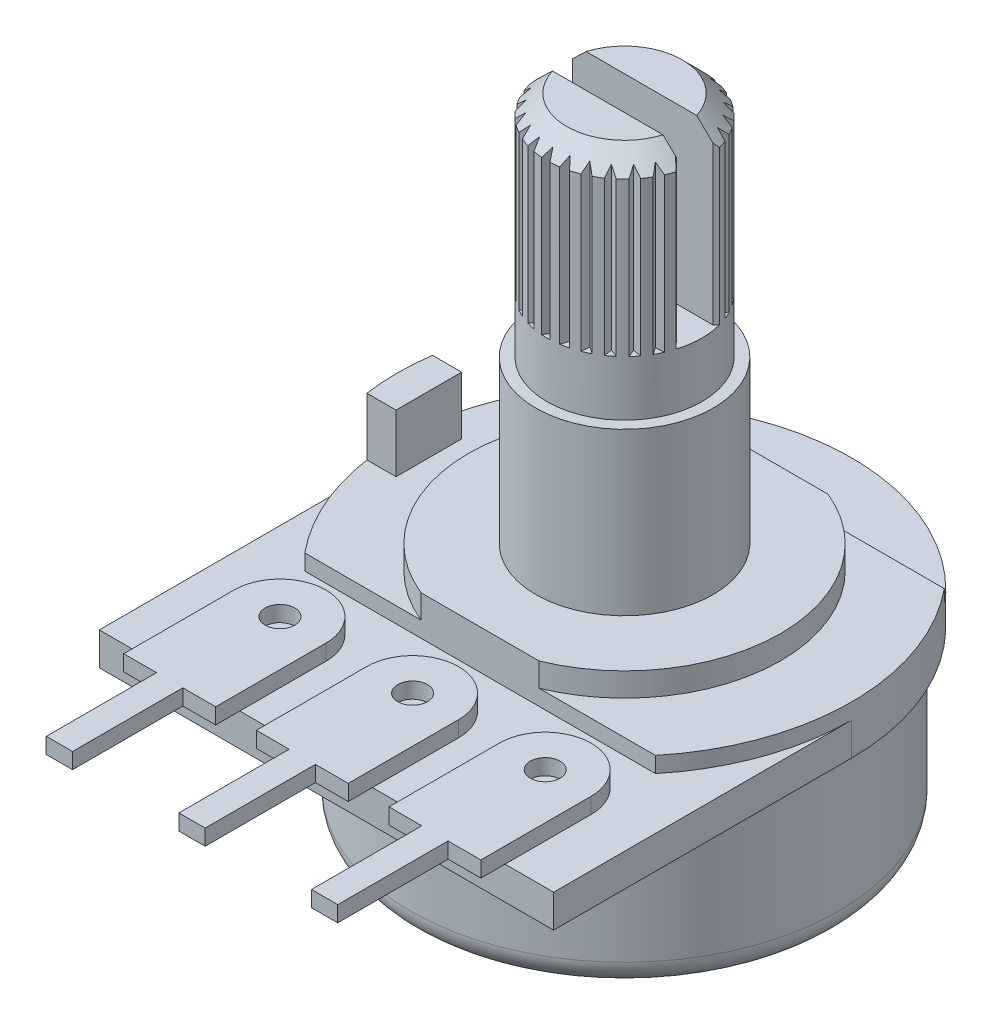
SolidWorks part; units mm, degrees
ref_plane "Alzado" through (0, 0, 0) normal (0, 0, 1) x (1, 0, 0)
ref_plane "Planta" through (0, 0, 0) normal (0, 1, 0) x (1, 0, 0)
ref_plane "Vista lateral" through (0, 0, 0) normal (1, 0, 0) x (0, 0, -1)
sketch "Croquis1" plane through (0, 0, 0) normal (0, 1, 0) x (1, 0, 0)
  circle A0 centre (0, 0) radius 8.15
  dimension "D1" = 16.3
extrude "Saliente-Extruir1" add sketch "Croquis1" along normal blind 6.3
fillet "Redondeo1" radius 1 1 edges at (0, 0, 8.15)
sketch "Croquis2" plane through (0, 6.3, 0) normal (0, 1, 0) x (1, 0, 0)
  line L0 (-8.65, 0) -> (-8.65, -11.35)
  line L1 (-8.65, -11.35) -> (8.65, -11.35)
  line L2 (8.65, -11.35) -> (8.65, 0)
  arc A0 (-8.65, 0) -> (8.65, 0) centre (0, 0) cw
  dimension "D1" = 8.65
  dimension "D2" = 11.35
extrude "Saliente-Extruir2" add sketch "Croquis2" along normal blind 1.25
sketch "Croquis11" plane through (0, 0, 0) normal (0, -1, 0) x (1, 0, 0)
  line L1 (-10.6457, -1) -> (-6.6543, -1)
  line L2 (-10.6457, -1) -> (-10.6457, 1)
  line L3 (-10.6457, 1) -> (-6.6543, 1)
  line L4 (-6.6543, -1) -> (-6.6543, 1)
  line L5 (-10.6457, -1) -> (-6.6543, 1) construction
  line L6 (-10.6457, 1) -> (-6.6543, -1) construction
  point P0 (-8.65, 0)
  dimension "D1" = 2
extrude "Cortar-Extruir3" cut sketch "Croquis11" against normal blind 2.6
sketch "Croquis3" plane through (0, 7.55, 0) normal (0, 1, 0) x (1, 0, 0)
  line L0 (-5.55, -16.47) -> (-5.55, -12.27)
  line L1 (-5.55, -12.27) -> (-6.8, -12.27)
  line L2 (-6.8, -12.27) -> (-6.8, -8.07)
  line L3 (-3.3, -8.07) -> (-3.3, -12.27)
  line L4 (-3.3, -12.27) -> (-4.55, -12.27)
  line L5 (-4.55, -12.27) -> (-4.55, -16.47)
  line L6 (-4.55, -16.47) -> (-5.55, -16.47)
  line L7 (-8.65, -11.35) -> (8.65, -11.35) construction
  line L8 (-0.5, -16.47) -> (-0.5, -12.27)
  line L9 (-0.5, -12.27) -> (-1.75, -12.27)
  line L10 (-1.75, -12.27) -> (-1.75, -8.07)
  line L11 (1.75, -8.07) -> (1.75, -12.27)
  line L12 (1.75, -12.27) -> (0.5, -12.27)
  line L13 (0.5, -12.27) -> (0.5, -16.47)
  line L14 (0.5, -16.47) -> (-0.5, -16.47)
  line L15 (4.55, -16.47) -> (4.55, -12.27)
  line L16 (4.55, -12.27) -> (3.3, -12.27)
  line L17 (3.3, -12.27) -> (3.3, -8.07)
  line L18 (6.8, -8.07) -> (6.8, -12.27)
  line L19 (6.8, -12.27) -> (5.55, -12.27)
  line L20 (5.55, -12.27) -> (5.55, -16.47)
  line L21 (5.55, -16.47) -> (4.55, -16.47)
  arc A0 (-6.8, -8.07) -> (-3.3, -8.07) centre (-5.05, -8.07) cw
  circle A1 centre (-5.05, -8.07) radius 0.5655
  arc A2 (-1.75, -8.07) -> (1.75, -8.07) centre (0, -8.07) cw
  circle A3 centre (0, -8.07) radius 0.5655
  arc A4 (3.3, -8.07) -> (6.8, -8.07) centre (5.05, -8.07) cw
  circle A5 centre (5.05, -8.07) radius 0.5655
  point P13 (0, -11.35)
  dimension "D1" = 1.75
  dimension "D2" = 1
  dimension "D3" = 4.2
  dimension "D4" = 5.12
  dimension "D5" = 4.2
  dimension "D6" = 3
extrude "Saliente-Extruir3" add sketch "Croquis3" along normal blind 0.6 separate body
sketch "Croquis4" plane through (0, 7.55, 0) normal (0, 1, 0) x (1, 0, 0)
  line L0 (-6.6763, -5.5) -> (6.6763, -5.5)
  line L1 (-6.6763, 5.5) -> (6.6763, 5.5)
  arc A0 (-6.6763, 5.5) -> (-6.6763, -5.5) centre (0, 0) ccw
  arc A1 (8.65, 0) -> (-8.65, 0) centre (0, 0) ccw construction
  arc A2 (6.6763, 5.5) -> (6.6763, -5.5) centre (0, 0) cw
  dimension "D1" = 11
extrude "Saliente-Extruir4" add sketch "Croquis4" along normal blind 0.6
sketch "Croquis5" plane through (0, 8.15, 0) normal (0, 1, 0) x (1, 0, 0)
  line L0 (6.6763, 5.5) -> (-6.6763, 5.5) construction
  line L1 (-6.6763, -5.5) -> (6.6763, -5.5) construction
  line L2 (-2.25, 5.5) -> (2.25, 5.5)
  line L3 (-2.25, -5.5) -> (2.25, -5.5)
  line L4 (-6.6763, -5.5) -> (6.6763, -5.5) construction
  arc A0 (-2.25, -5.5) -> (-2.25, 5.5) centre (0, 0) cw
  arc A1 (2.25, 5.5) -> (2.25, -5.5) centre (0, 0) cw
  dimension "D1" = 4.5
extrude "Saliente-Extruir5" add sketch "Croquis5" along normal blind 0.9
sketch "Croquis6" plane through (0, 9.05, 0) normal (0, 1, 0) x (1, 0, 0)
  circle A0 centre (0, 0) radius 3.375
  dimension "D1" = 6.75
extrude "Saliente-Extruir6" add sketch "Croquis6" along normal blind 6.15
sketch "Croquis7" plane through (0, 15.2, 0) normal (0, 1, 0) x (1, 0, 0)
  circle A0 centre (0, 0) radius 2.95
  dimension "D1" = 5.9
extrude "Saliente-Extruir7" add sketch "Croquis7" along normal blind 8.7
chamfer "Chaflán1" distance 0.75 angle 45 1 edges at (0, 23.9, 2.95)
sketch "Croquis8" plane through (0, 23.9, 0) normal (0, 1, 0) x (1, 0, 0)
  line L1 (-6.8143, 0.64) -> (6.8143, 0.64)
  line L2 (-6.8143, 0.64) -> (-6.8143, -0.64)
  line L3 (-6.8143, -0.64) -> (6.8143, -0.64)
  line L4 (6.8143, 0.64) -> (6.8143, -0.64)
  line L5 (-6.8143, 0.64) -> (6.8143, -0.64) construction
  line L6 (-6.8143, -0.64) -> (6.8143, 0.64) construction
  point P0 (0, 0)
  dimension "D1" = 1.28
extrude "Cortar-Extruir1" cut sketch "Croquis8" against normal blind 6.6
sketch "Croquis9" plane through (0, 23.9, 0) normal (0, 1, 0) x (1, 0, 0)
  line L0 (0.0546, 2.67) -> (0.314, 3.1192)
  line L1 (0.314, 3.1192) -> (-0.2048, 3.1192)
  line L2 (-0.2048, 3.1192) -> (0.0546, 2.67)
  line L3 (0.6474, 2.5909) -> (1.0002, 2.9712)
  line L4 (1.0002, 2.9712) -> (0.4944, 3.0866)
  line L5 (0.4944, 3.0866) -> (0.6474, 2.5909)
  line L6 (1.2077, 2.3819) -> (1.6363, 2.6741)
  line L7 (1.6363, 2.6741) -> (1.1689, 2.8992)
  line L8 (1.1689, 2.8992) -> (1.2077, 2.3819)
  line L9 (1.7074, 2.0534) -> (2.1903, 2.2429)
  line L10 (2.1903, 2.2429) -> (1.7847, 2.5664)
  line L11 (1.7847, 2.5664) -> (1.7074, 2.0534)
  line L12 (2.1215, 1.622) -> (2.6345, 1.6993)
  line L13 (2.6345, 1.6993) -> (2.311, 2.1049)
  line L14 (2.311, 2.1049) -> (2.1215, 1.622)
  line L15 (2.4292, 1.1093) -> (2.9466, 1.0705)
  line L16 (2.9466, 1.0705) -> (2.7215, 1.5379)
  line L17 (2.7215, 1.5379) -> (2.4292, 1.1093)
  line L18 (2.6152, 0.5409) -> (3.1109, 0.388)
  line L19 (3.1109, 0.388) -> (2.9955, 0.8937)
  line L20 (2.9955, 0.8937) -> (2.6152, 0.5409)
  line L21 (2.67, -0.0546) -> (3.1192, -0.314)
  line L22 (3.1192, -0.314) -> (3.1192, 0.2048)
  line L23 (3.1192, 0.2048) -> (2.67, -0.0546)
  line L24 (2.5909, -0.6474) -> (2.9712, -1.0002)
  line L25 (2.9712, -1.0002) -> (3.0866, -0.4944)
  line L26 (3.0866, -0.4944) -> (2.5909, -0.6474)
  line L27 (2.3819, -1.2077) -> (2.6741, -1.6363)
  line L28 (2.6741, -1.6363) -> (2.8992, -1.1689)
  line L29 (2.8992, -1.1689) -> (2.3819, -1.2077)
  line L30 (2.0534, -1.7074) -> (2.2429, -2.1903)
  line L31 (2.2429, -2.1903) -> (2.5664, -1.7847)
  line L32 (2.5664, -1.7847) -> (2.0534, -1.7074)
  line L33 (1.622, -2.1215) -> (1.6993, -2.6345)
  line L34 (1.6993, -2.6345) -> (2.1049, -2.311)
  line L35 (2.1049, -2.311) -> (1.622, -2.1215)
  line L36 (1.1093, -2.4292) -> (1.0705, -2.9466)
  line L37 (1.0705, -2.9466) -> (1.5379, -2.7215)
  line L38 (1.5379, -2.7215) -> (1.1093, -2.4292)
  line L39 (0.5409, -2.6152) -> (0.388, -3.1109)
  line L40 (0.388, -3.1109) -> (0.8937, -2.9955)
  line L41 (0.8937, -2.9955) -> (0.5409, -2.6152)
  line L42 (-0.0546, -2.67) -> (-0.314, -3.1192)
  line L43 (-0.314, -3.1192) -> (0.2048, -3.1192)
  line L44 (0.2048, -3.1192) -> (-0.0546, -2.67)
  line L45 (-0.6474, -2.5909) -> (-1.0002, -2.9712)
  line L46 (-1.0002, -2.9712) -> (-0.4944, -3.0866)
  line L47 (-0.4944, -3.0866) -> (-0.6474, -2.5909)
  line L48 (-1.2077, -2.3819) -> (-1.6363, -2.6741)
  line L49 (-1.6363, -2.6741) -> (-1.1689, -2.8992)
  line L50 (-1.1689, -2.8992) -> (-1.2077, -2.3819)
  line L51 (-1.7074, -2.0534) -> (-2.1903, -2.2429)
  line L52 (-2.1903, -2.2429) -> (-1.7847, -2.5664)
  line L53 (-1.7847, -2.5664) -> (-1.7074, -2.0534)
  line L54 (-2.1215, -1.622) -> (-2.6345, -1.6993)
  line L55 (-2.6345, -1.6993) -> (-2.311, -2.1049)
  line L56 (-2.311, -2.1049) -> (-2.1215, -1.622)
  line L57 (-2.4292, -1.1093) -> (-2.9466, -1.0705)
  line L58 (-2.9466, -1.0705) -> (-2.7215, -1.5379)
  line L59 (-2.7215, -1.5379) -> (-2.4292, -1.1093)
  line L60 (-2.6152, -0.5409) -> (-3.1109, -0.388)
  line L61 (-3.1109, -0.388) -> (-2.9955, -0.8937)
  line L62 (-2.9955, -0.8937) -> (-2.6152, -0.5409)
  line L63 (-2.67, 0.0546) -> (-3.1192, 0.314)
  line L64 (-3.1192, 0.314) -> (-3.1192, -0.2048)
  line L65 (-3.1192, -0.2048) -> (-2.67, 0.0546)
  line L66 (-2.5909, 0.6474) -> (-2.9712, 1.0002)
  line L67 (-2.9712, 1.0002) -> (-3.0866, 0.4944)
  line L68 (-3.0866, 0.4944) -> (-2.5909, 0.6474)
  line L69 (-2.3819, 1.2077) -> (-2.6741, 1.6363)
  line L70 (-2.6741, 1.6363) -> (-2.8992, 1.1689)
  line L71 (-2.8992, 1.1689) -> (-2.3819, 1.2077)
  line L72 (-2.0534, 1.7074) -> (-2.2429, 2.1903)
  line L73 (-2.2429, 2.1903) -> (-2.5664, 1.7847)
  line L74 (-2.5664, 1.7847) -> (-2.0534, 1.7074)
  line L75 (-1.622, 2.1215) -> (-1.6993, 2.6345)
  line L76 (-1.6993, 2.6345) -> (-2.1049, 2.311)
  line L77 (-2.1049, 2.311) -> (-1.622, 2.1215)
  line L78 (-1.1093, 2.4292) -> (-1.0705, 2.9466)
  line L79 (-1.0705, 2.9466) -> (-1.5379, 2.7215)
  line L80 (-1.5379, 2.7215) -> (-1.1093, 2.4292)
  line L81 (-0.5409, 2.6152) -> (-0.388, 3.1109)
  line L82 (-0.388, 3.1109) -> (-0.8937, 2.9955)
  line L83 (-0.8937, 2.9955) -> (-0.5409, 2.6152)
  point P2 (0.0546, 3.1192)
  point P88 (0, 0)
  dimension "D1" = 60
  dimension "D2" = 28
extrude "Cortar-Extruir2" cut sketch "Croquis9" against normal blind 6.6
sketch "Croquis10" plane through (0, 8.15, 0) normal (0, 1, 0) x (1, 0, 0)
  line L0 (-8.5592, 1.25) -> (-7.45, 1.25)
  line L1 (-7.45, 1.25) -> (-7.45, -1.25)
  line L2 (-7.45, -1.25) -> (-8.5592, -1.25)
  arc A0 (-8.5592, 1.25) -> (-8.5592, -1.25) centre (0, 0) ccw
  arc A1 (-6.6763, 5.5) -> (-6.6763, -5.5) centre (0, 0) ccw construction
  point P8 (-8.65, 0)
  point P10 (-7.45, 0)
  dimension "D1" = 1.2
  dimension "D2" = 2.5
extrude "Saliente-Extruir8" add sketch "Croquis10" along normal blind 2.2
